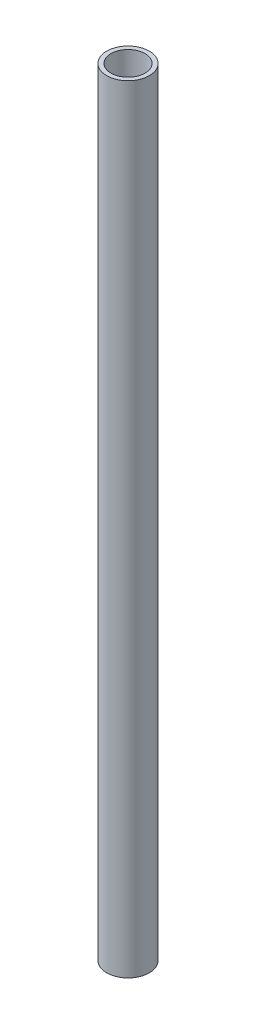
SolidWorks part; units mm, degrees
ref_plane "Front Plane" through (0, 0, 0) normal (0, 0, 1) x (1, 0, 0)
ref_plane "Top Plane" through (0, 0, 0) normal (0, 1, 0) x (1, 0, 0)
ref_plane "Right Plane" through (0, 0, 0) normal (1, 0, 0) x (0, 0, -1)
sketch "Sketch1" plane through (0, 0, 0) normal (0, 1, 0) x (1, 0, 0)
  circle A0 centre (0, 0) radius 16.7005
  circle A1 centre (0, 0) radius 13.335
  dimension "D1" = 33.401
  dimension "D2" = 26.67
extrude "Boss-Extrude1" add sketch "Sketch1" along normal blind 609.6
